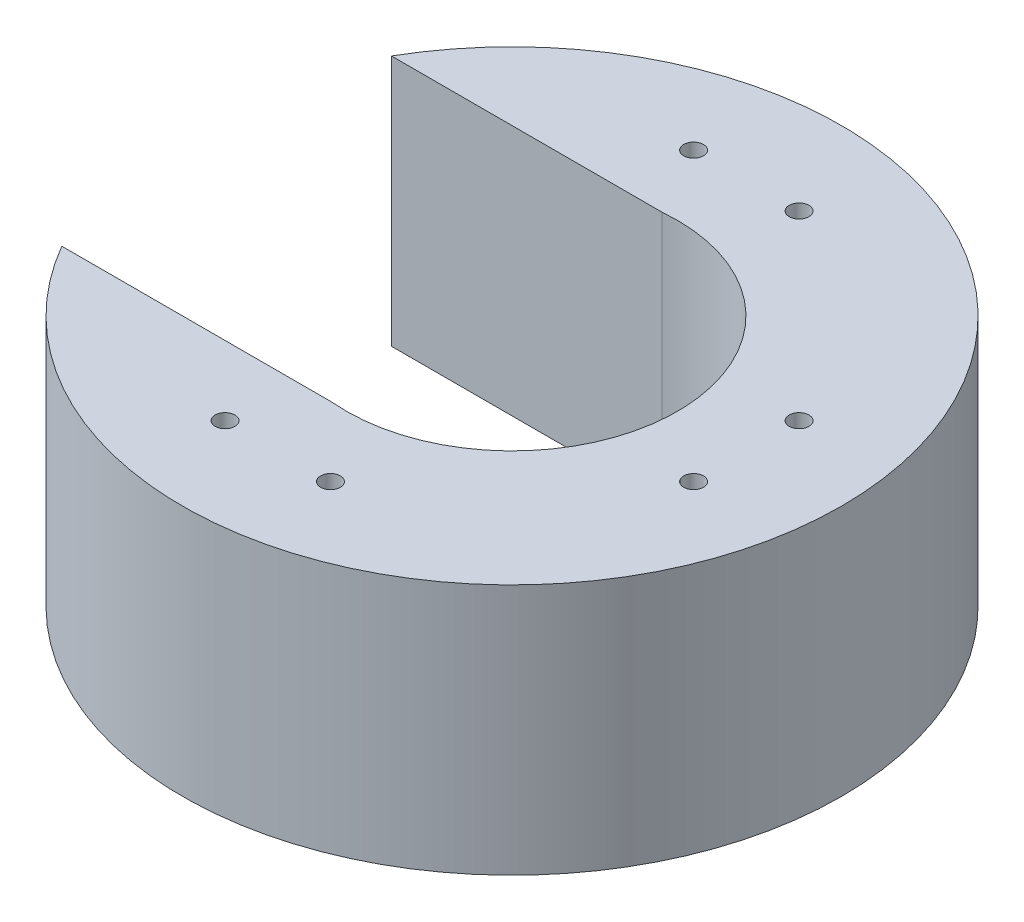
SolidWorks part; units mm, degrees
ref_plane "Front Plane" through (0, 0, 0) normal (0, 0, 1) x (1, 0, 0)
ref_plane "Top Plane" through (0, 0, 0) normal (0, 1, 0) x (1, 0, 0)
ref_plane "Right Plane" through (0, 0, 0) normal (1, 0, 0) x (0, 0, -1)
sketch "Sketch1" plane through (0, 0, 0) normal (0, 1, 0) x (1, 0, 0)
  line L0 (0, 0) -> (0, -35.55) construction
  line L4 (-43.3, 25.0022) -> (-19.5899, 15.6922)
  line L5 (-43.3, -25.0022) -> (-19.5899, -15.6922)
  line L6 (0, 0) -> (-4.4925, 0) construction
  line L7 (0, 0) -> (35.55, 0) construction
  arc A0 (-43.3, -25.0022) -> (-43.3, 25.0022) centre (0, 0) ccw
  arc A1 (-19.5899, -15.6922) -> (-19.5899, 15.6922) centre (0, 0) ccw
  circle A2 centre (8, -35.55) radius 1.5
  circle A3 centre (-8, -35.55) radius 1.5
  circle A4 centre (8, 35.55) radius 1.5
  circle A5 centre (-8, 35.55) radius 1.5
  circle A6 centre (35.55, 8) radius 1.5
  circle A7 centre (35.55, -8) radius 1.5
  point P7 (-43.3, 0)
  dimension "D1" = 100
  dimension "D3" = 50.2
  dimension "D4" = 3
  dimension "D5" = 8
  dimension "D2" = 35.55
  dimension "D6" = 35.55
  dimension "D7" = 8
extrude "Boss-Extrude1" add sketch "Sketch1" along normal blind 38.15
ref_plane "Plane1" through (-43.3, 0, 0) normal (-1, 0, 0) x (0, 0, 1)
sketch "Sketch4" plane through (-43.3, 0, 0) normal (-1, 0, 0) x (0, 0, 1)
  line L0 (-25.0022, 38.15) -> (-25.0022, 0)
  line L1 (-25.0022, 0) -> (-15.6922, 0)
  line L2 (-15.6922, 0) -> (-15.6922, 38.15)
  line L3 (-15.6922, 38.15) -> (-25.0022, 38.15)
  line L4 (15.6922, 38.15) -> (15.6922, 0)
  line L5 (15.6922, 0) -> (25.0022, 0)
  line L6 (25.0022, 0) -> (25.0022, 38.15)
  line L7 (25.0022, 38.15) -> (15.6922, 38.15)
extrude "Cut-Extrude2" cut sketch "Sketch4" against normal blind 45
